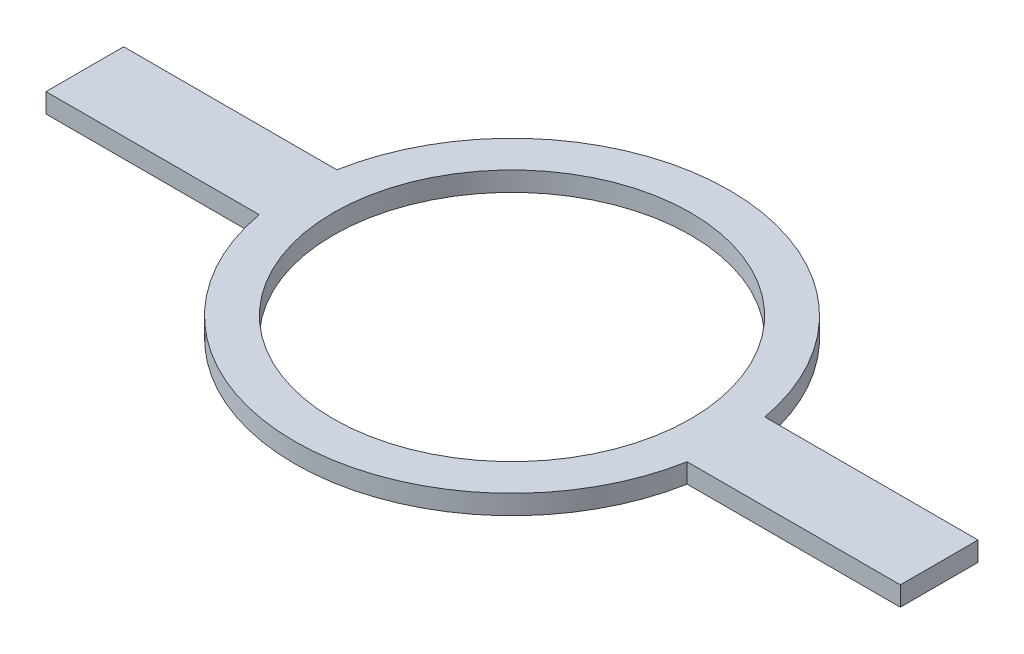
SolidWorks part; units mm, degrees
ref_plane "Front Plane" through (0, 0, 0) normal (0, 0, 1) x (1, 0, 0)
ref_plane "Top Plane" through (0, 0, 0) normal (0, 1, 0) x (1, 0, 0)
ref_plane "Right Plane" through (0, 0, 0) normal (1, 0, 0) x (0, 0, -1)
sketch "Sketch1" plane through (0, 0, 0) normal (0, 1, 0) x (1, 0, 0)
  line L0 (69.9769, 12.7) -> (139.7, 12.7)
  line L1 (-139.7, 12.7) -> (-69.9769, 12.7)
  line L2 (-139.7, 12.7) -> (-139.7, -12.7)
  line L3 (-139.7, -12.7) -> (-69.9769, -12.7)
  line L4 (139.7, 12.7) -> (139.7, -12.7)
  line L5 (-139.7, 12.7) -> (139.7, -12.7) construction
  line L6 (-139.7, -12.7) -> (139.7, 12.7) construction
  line L7 (69.9769, -12.7) -> (139.7, -12.7)
  circle A0 centre (0, 0) radius 58.42
  arc A1 (-69.9769, -12.7) -> (69.9769, -12.7) centre (0, 0) ccw
  arc A2 (69.9769, 12.7) -> (-69.9769, 12.7) centre (0, 0) ccw
  point P0 (0, 0)
  dimension "D3" = 116.84
  dimension "D4" = 12.7
  dimension "D1" = 279.4
  dimension "D2" = 25.4
extrude "Boss-Extrude1" add sketch "Sketch1" along normal blind 6.35
